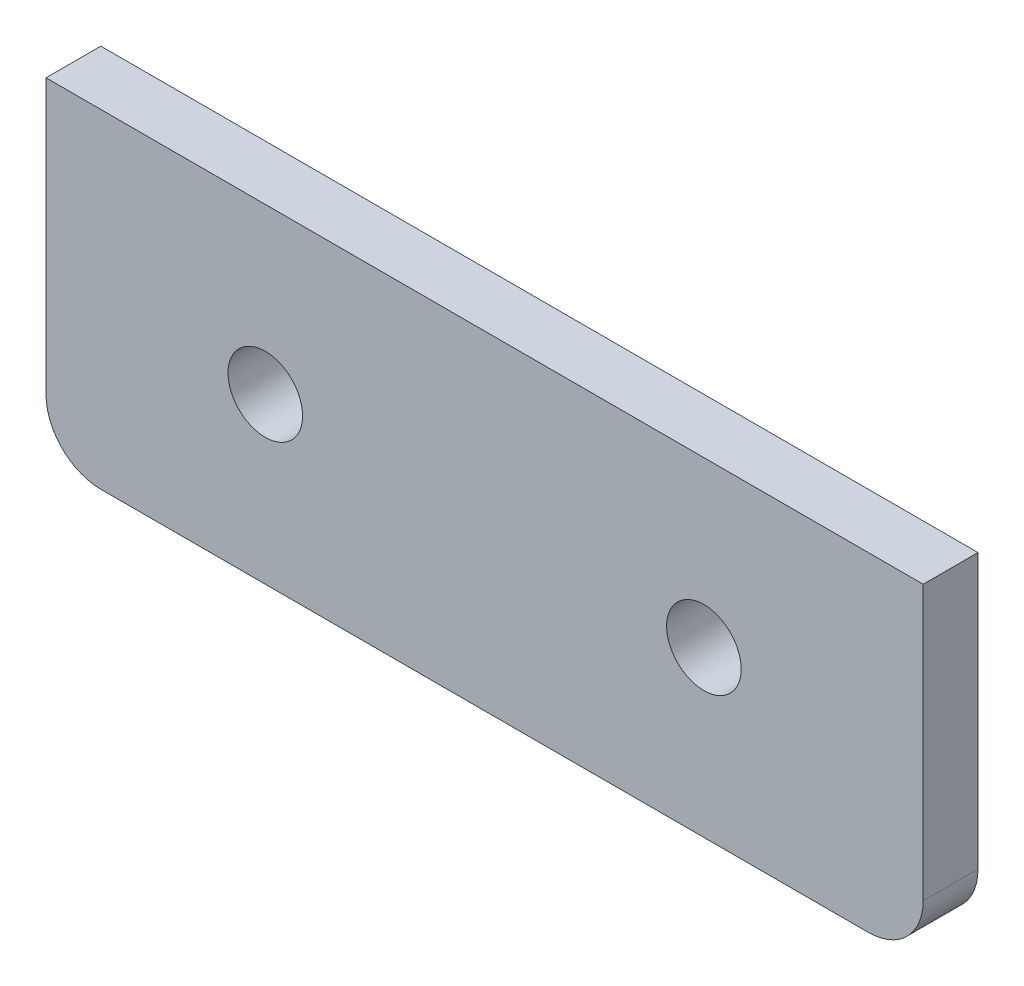
SolidWorks part; units mm, degrees
ref_plane "Ön Düzlem" through (0, 0, 0) normal (0, 0, 1) x (1, 0, 0)
ref_plane "Üst Düzlem" through (0, 0, 0) normal (0, 1, 0) x (1, 0, 0)
ref_plane "Sağ Düzlem" through (0, 0, 0) normal (1, 0, 0) x (0, 0, -1)
sketch "Çizim1" plane through (0, 0, 0) normal (0, 0, 1) x (1, 0, 0)
  line L1 (-40, 15) -> (40, 15)
  line L2 (-40, 15) -> (-40, -15)
  line L3 (-40, -15) -> (40, -15)
  line L4 (40, 15) -> (40, -15)
  line L5 (-40, 15) -> (40, -15) construction
  line L6 (-40, -15) -> (40, 15) construction
  point P0 (0, 0)
  dimension "D1" = 80
  dimension "D2" = 30
extrude "Yükseklik-Ekstrüzyon1" add sketch "Çizim1" along normal blind 5
fillet "Radyus2" radius 5 2 edges at (40, -15, 2.5) (-40, -15, 2.5)
sketch "Çizim2" plane through (0, 0, 5) normal (0, 0, 1) x (1, 0, 0)
  circle A0 centre (-20, 0) radius 3.4
  circle A1 centre (20, 0) radius 3.4
  dimension "D1" = 6.8
  dimension "D2" = 6.8
  dimension "D3" = 20
  dimension "D4" = 20
extrude "Kes-Ekstrüzyon1" cut sketch "Çizim2" against normal blind 8
cosmetic thread "Kozmetik Diş Açma1" parameters "D2"=8
cosmetic thread "Kozmetik Diş Açma2" parameters "D2"=8
